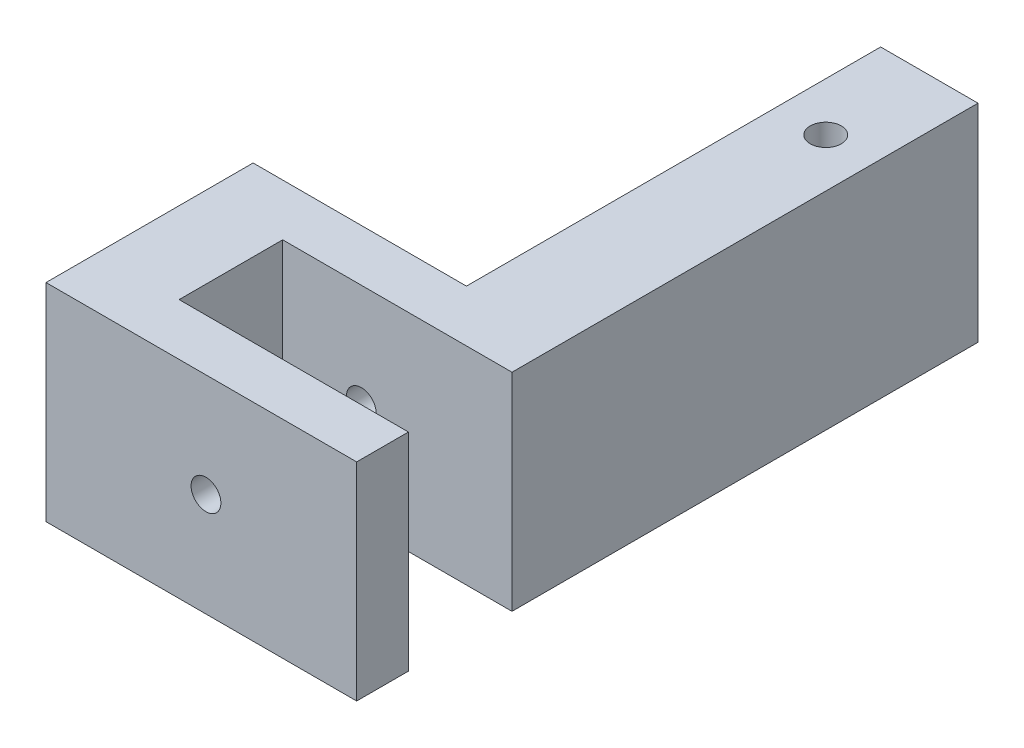
SolidWorks part; units mm, degrees
ref_plane "Front Plane" through (0, 0, 0) normal (0, 0, 1) x (1, 0, 0)
ref_plane "Top Plane" through (0, 0, 0) normal (0, 1, 0) x (1, 0, 0)
ref_plane "Right Plane" through (0, 0, 0) normal (1, 0, 0) x (0, 0, -1)
sketch "Sketch1" plane through (0, 0, 0) normal (0, 1, 0) x (1, 0, 0)
  line L4 (0, 0) -> (-28.1243, 0)
  line L5 (-28.1243, 0) -> (-28.1243, 12.7)
  line L6 (-28.1243, 12.7) -> (0, 12.7)
  line L7 (0, 12.7) -> (0, 19.05)
  line L9 (-38.1, 19.05) -> (-38.1, 7.0311)
  line L10 (-38.1, 7.0311) -> (-38.1, -6.35)
  line L11 (-38.1, -6.35) -> (0, -6.35)
  line L12 (0, -6.35) -> (0, 0)
  line L13 (-11.9388, 19.05) -> (-11.9388, 69.85)
  line L14 (-11.9388, 69.85) -> (0, 69.85)
  line L15 (0, 69.85) -> (0, 19.05)
  line L16 (0, 44.45) -> (-11.9388, 44.45) construction
  line L17 (-11.9388, 44.45) -> (0, 69.85) construction
  line L18 (-11.9388, 69.85) -> (0, 44.45) construction
  line L20 (-11.9388, 19.05) -> (0, 19.05) construction
  line L23 (-38.1, 19.05) -> (-11.9388, 19.05)
  circle A0 centre (-5.9694, 57.15) radius 1.905
  dimension "D6" = 3.81
  dimension "D1" = 12.7
  dimension "D2" = 6.35
  dimension "D3" = 6.35
  dimension "D4" = 38.1
  dimension "D5" = 50.8
extrude "Boss-Extrude2" add sketch "Sketch1" along normal blind 25.4
sketch "Sketch2" plane through (0, 0, -19.05) normal (0, 0, -1) x (-1, 0, 0)
  line L0 (11.9388, 25.4) -> (38.1, 0) construction
  line L1 (11.9388, 0) -> (38.1, 25.4) construction
  line L2 (25.0194, 12.7) -> (11.9388, 12.7) construction
  line L3 (11.9388, 25.4) -> (11.9388, 0) construction
hole_wizard "CSK for #6 Oval Head Machine Screw1" positions "Sketch9" profile "Sketch10" countersink size "#6" standard "ANSI Inch" end condition through all
sketch "Sketch9" plane through (0, 0, -19.05) normal (0, 0, -1) x (-1, 0, 0)
  line L0 (25.0194, 12.7) -> (11.9388, 12.7) construction
  point P0 (18.4791, 12.7)
sketch "Sketch10" plane through (-18.4791, 12.7, -19.05) normal (1, 0, 0) x (0, 1, 0)
  line L0 (0, 0) -> (0, 25.4)
  line L1 (0, 25.4) -> (1.8288, 25.4)
  line L2 (1.8288, 25.4) -> (1.8288, 1.9723)
  line L3 (1.8288, 1.9723) -> (3.5433, 0)
  line L5 (3.5433, 0) -> (0, 0)
  line L6 (-1.8288, 1.9723) -> (-3.5433, 0) construction
  line L11 (0, -6.35) -> (0, 107.95) construction
  dimension "Thru Hole Dia." = 3.6576
  dimension "Thru Hole Depth" = 25.4
  dimension "Near C'Sink Dia." = 7.0866
  dimension "Near C'Sink Angle" = 82
